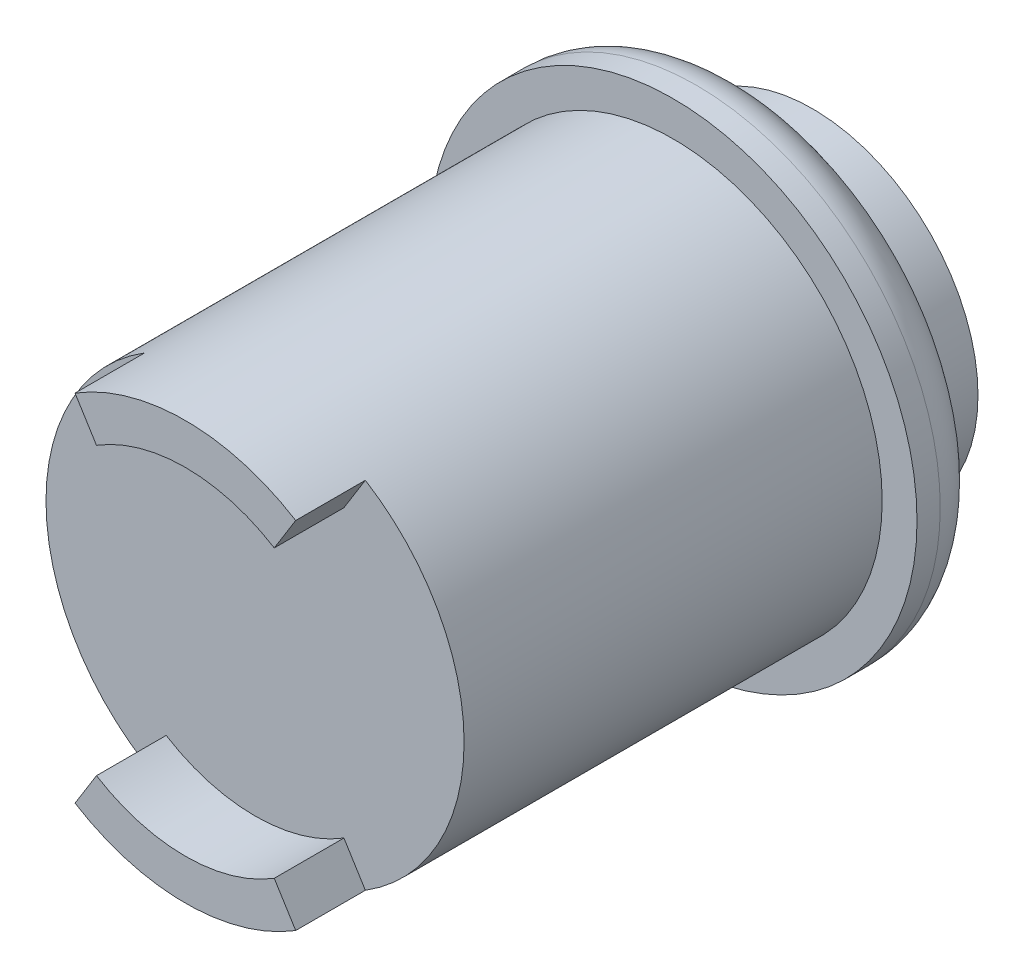
SolidWorks part; units mm, degrees
ref_plane "Front Plane" through (0, 0, 0) normal (0, 0, 1) x (1, 0, 0)
ref_plane "Top Plane" through (0, 0, 0) normal (0, 1, 0) x (1, 0, 0)
ref_plane "Right Plane" through (0, 0, 0) normal (1, 0, 0) x (0, 0, -1)
sketch "Sketch1" plane through (0, 0, 0) normal (0, 0, 1) x (1, 0, 0)
  circle A0 centre (0, 0) radius 14.2875
  dimension "D1" = 28.575
extrude "Boss-Extrude1" add sketch "Sketch1" along normal blind 33.3375
sketch "Sketch2" plane through (0, 0, 0) normal (0, 0, -1) x (-1, 0, 0)
  circle A0 centre (0, 0) radius 16.6687
  dimension "D1" = 33.3375
extrude "Boss-Extrude2" add sketch "Sketch2" along normal blind 4.7625
fillet "Fillet1" radius 3.175 1 edges at (-16.6687, 0, -4.7625)
sketch "Sketch3" plane through (0, 0, -4.7625) normal (0, 0, -1) x (-1, 0, 0)
  circle A0 centre (0, 0) radius 11.3109
  dimension "D1" = 22.6219
extrude "Boss-Extrude3" add sketch "Sketch3" along normal blind 4.7625
sketch "Sketch4" plane through (0, 0, 33.3375) normal (0, 0, 1) x (1, 0, 0)
  line L0 (-7.5406, 12.1356) -> (-6.0744, 9.7759)
  line L1 (-6.0744, 9.7759) -> (6.0744, -9.7759) construction
  line L2 (6.0744, -9.7759) -> (7.5406, -12.1356)
  line L3 (0, 0.7133) -> (0, 50000.7133) construction
  line L4 (-6.0744, -9.7759) -> (-7.5406, -12.1356)
  line L5 (7.5406, 12.1356) -> (6.0744, 9.7759)
  arc A0 (-7.5406, 12.1356) -> (-7.5406, -12.1356) centre (0, 0) ccw
  arc A1 (-6.0744, -9.7759) -> (6.0744, -9.7759) centre (0, 0) ccw
  circle A2 centre (0, 0) radius 14.2875 construction
  arc A3 (7.5406, -12.1356) -> (7.5406, 12.1356) centre (0, 0) ccw
  arc A4 (6.0744, 9.7759) -> (-6.0744, 9.7759) centre (0, 0) ccw
  dimension "D1" = 23.0188
  dimension "D2" = 7.5406
extrude "Cut-Extrude1" cut sketch "Sketch4" against normal blind 4.7625
